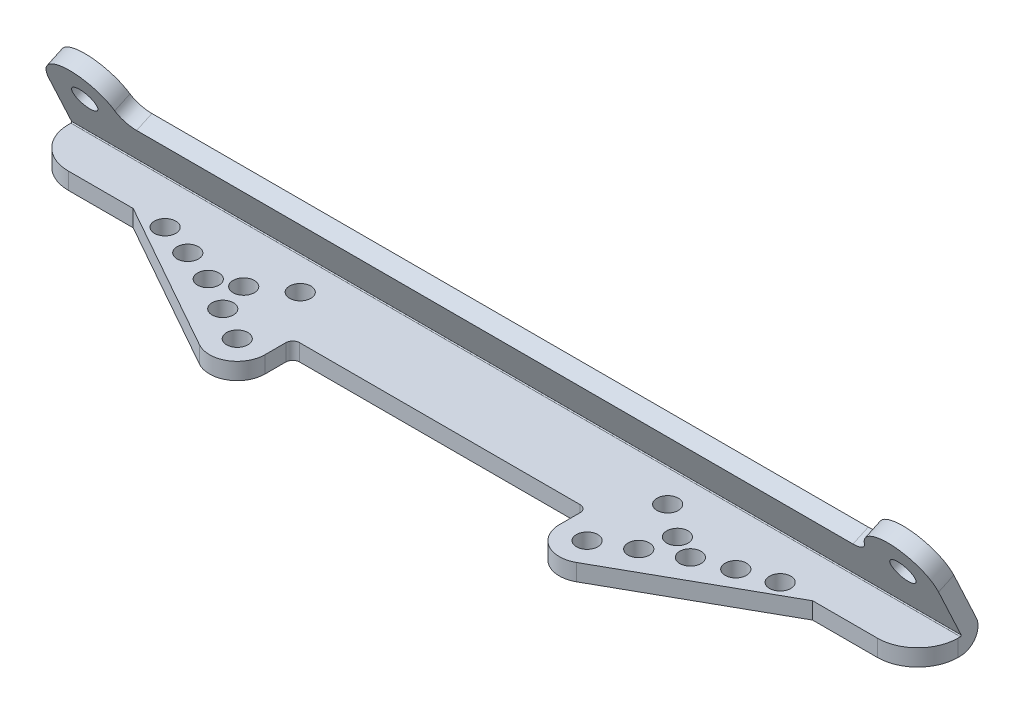
SolidWorks part; units mm, degrees
ref_plane "Front Plane" through (0, 0, 0) normal (0, 0, 1) x (1, 0, 0)
ref_plane "Top Plane" through (0, 0, 0) normal (0, 1, 0) x (1, 0, 0)
ref_plane "Right Plane" through (0, 0, 0) normal (1, 0, 0) x (0, 0, -1)
sketch "Sketch1" plane through (0, 0, 0) normal (1, 0, 0) x (0, 0, -1)
  line L0 (-22.947, 0) -> (-3.987, 0)
  line L1 (-1.685, 3.6135) -> (-7.1159, 15.26)
  line L2 (-22.947, 2.42) -> (-3.987, 2.42)
  line L3 (-3.8782, 2.5907) -> (-9.3091, 14.2373)
  line L4 (-22.947, 2.42) -> (-22.947, 0)
  line L5 (-9.3091, 14.2373) -> (-7.1159, 15.26)
  arc A0 (-3.987, 0) -> (-1.685, 3.6135) centre (-3.987, 2.54) ccw
  arc A1 (-3.987, 2.42) -> (-3.8782, 2.5907) centre (-3.987, 2.54) ccw
  point P6 (0, 0)
  point P12 (-1.447, 2.54)
  point P13 (-17.2201, 13.5342)
  dimension "D1" = 2.54
  dimension "D3" = 15.26
  dimension "D4" = 21.5
  dimension "D5" = 65
  dimension "D2" = 2.42
extrude "Boss-Extrude1" add sketch "Sketch1" along normal mid plane 128.3 contours L3 L5 L1 A0 L0 L4 L2 A1
sketch "Sketch2" plane through (0, 0, 0) normal (0, 0.4226, -0.9063) x (-1, 0, 0)
  line L0 (-64.15, 16.8375) -> (64.15, 16.8375) construction
  line L1 (64.15, 3.987) -> (64.15, 16.8375) construction
  line L2 (-64.15, 3.987) -> (-64.15, 16.8375) construction
  line L3 (64.15, 11.6875) -> (64.15, 16.8375)
  line L4 (-64.15, 11.6875) -> (-64.15, 16.8375)
  line L5 (-64.15, 16.8375) -> (64.15, 16.8375)
  line L6 (0, 8.393) -> (0, -8.393) construction
  line L7 (-51.6583, 11.3375) -> (51.6583, 11.3375)
  arc A0 (-54.0576, 13.1349) -> (-64.15, 11.6875) centre (-59, 11.6875) ccw
  arc A1 (54.0576, 13.1349) -> (64.15, 11.6875) centre (59, 11.6875) cw
  arc A2 (51.6583, 11.3375) -> (54.0576, 13.1349) centre (51.6583, 13.8375) ccw
  arc A3 (-51.6583, 11.3375) -> (-54.0576, 13.1349) centre (-51.6583, 13.8375) cw
  circle A4 centre (-59, 11.6875) radius 1.75
  circle A5 centre (59, 11.6875) radius 1.75
  line M9 (64.15, 3.987) -> (64.15, 16.8375)
  line M10 (64.15, 16.8375) -> (-64.15, 16.8375)
  line M11 (-64.15, 16.8375) -> (-64.15, 3.987)
  dimension "D1" = 2.5
  dimension "D2" = 5.5
  dimension "D4" = 3.5
  dimension "D3" = 118
extrude "Cut-Extrude1" cut sketch "Sketch2" against normal up to surface (2.42 mm away) contours A0 L5 M11 | A3 L7 A2 A1 L5 A0 | A1 M10 M9 | A4 | A5 up to face at (0, 8.414, 6.5937)
sketch "Sketch3" plane through (0, 0, 0) normal (0, -1, 0) x (1, 0, 0)
  line L0 (-58.35, 10.147) -> (-49, 10.147)
  line L1 (-49, 10.147) -> (-27.1885, 22.3948)
  line L2 (-21.23, 18.907) -> (-21.23, 15.907)
  line L3 (-20.23, 14.907) -> (20.23, 14.907)
  line L4 (-64.15, 22.947) -> (-64.15, 3.987)
  line L5 (-64.15, 3.987) -> (64.15, 3.987)
  line L6 (64.15, 3.987) -> (64.15, 22.947)
  line L7 (64.15, 22.947) -> (-64.15, 22.947)
  line L8 (-64.15, 22.947) -> (-64.15, 4.347)
  line L10 (64.15, 3.987) -> (64.15, 22.947)
  line L11 (64.15, 22.947) -> (-64.15, 22.947)
  line L12 (-64.15, 1.447) -> (64.15, 1.447) construction
  line L13 (0, -8.393) -> (0, 8.393) construction
  line L15 (21.23, 18.907) -> (21.23, 15.907)
  line L16 (49, 10.147) -> (27.1885, 22.3948)
  line L17 (58.35, 10.147) -> (49, 10.147)
  arc A0 (-58.35, 10.147) -> (-64.15, 4.347) centre (-58.35, 4.347) ccw
  arc A1 (-27.1885, 22.3948) -> (-21.23, 18.907) centre (-25.23, 18.907) cw
  arc A2 (-21.23, 15.907) -> (-20.23, 14.907) centre (-20.23, 15.907) ccw
  circle A3 centre (-25.23, 18.907) radius 1.54
  arc A4 (21.23, 15.907) -> (20.23, 14.907) centre (20.23, 15.907) cw
  arc A5 (27.1885, 22.3948) -> (21.23, 18.907) centre (25.23, 18.907) ccw
  arc A6 (58.35, 10.147) -> (64.15, 4.347) centre (58.35, 4.347) cw
  point P13 (-21.23, 25.7406)
  point P20 (-25.23, 22.907)
  point P24 (1.6824, 14.907)
  point P34 (0, 0)
  line M11 (-64.15, 22.947) -> (-64.15, 3.987)
  line M14 (64.15, 22.947) -> (-64.15, 22.947)
  dimension "D2" = 4
  dimension "D3" = 1
  dimension "D5" = 5.8
  dimension "D10" = 3.08
  dimension "D4" = 8.7
  dimension "D6" = 21.23
  dimension "D7" = 49
  dimension "D8" = 13.46
  dimension "D9" = 21.46
  dimension "D1" = 0
extrude "Cut-Extrude2" cut sketch "Sketch3" against normal up to surface (2.42 mm away) contours L17 A6 L10 A0 L0 L1 A1 L2 A2 L3 A4 L15 A5 L16 M14 M11 up to face at (0, 2.42, 13.467)
sketch "Sketch4" plane through (0, 0, 0) normal (0, -1, 0) x (1, 0, 0)
  line L0 (-44.3541, 10.1868) -> (-45.4508, 12.14) construction
  line L1 (-49, 10.147) -> (-27.1885, 22.3948) construction
  line L2 (-39.5217, 11.7535) -> (-41.1081, 14.5785) construction
  circle A0 centre (-25.23, 18.907) radius 1.54
  circle A1 centre (-30, 16.2285) radius 1.54
  circle A2 centre (-34.77, 13.55) radius 1.54
  circle A3 centre (-31.2756, 11.934) radius 1.54
  circle A4 centre (-39.5217, 11.7535) radius 1.54
  circle A5 centre (-44.3541, 10.1868) radius 1.54
  circle A6 centre (-26.4987, 8.557) radius 1.54
  point P16 (-40.2757, 13.0962)
  point P18 (-45.1081, 11.5296)
  dimension "D3" = 3.08
  dimension "D2" = 30
  dimension "D4" = 5.08
  dimension "D5" = 5.08
  dimension "D6" = 1.7
  dimension "D7" = 0.7
  dimension "D8" = 5.85
  dimension "D9" = 3.85
  dimension "D10" = 4.48
  dimension "D11" = 10.35
  dimension "D1" = 3
extrude "Cut-Extrude3" cut sketch "Sketch4" against normal up to surface (2.42 mm away) up to face at (0, 2.42, 12.9308)
mirror "Mirror1" about plane through (0, 0, 0) normal (1, 0, 0) of "Cut-Extrude3"
